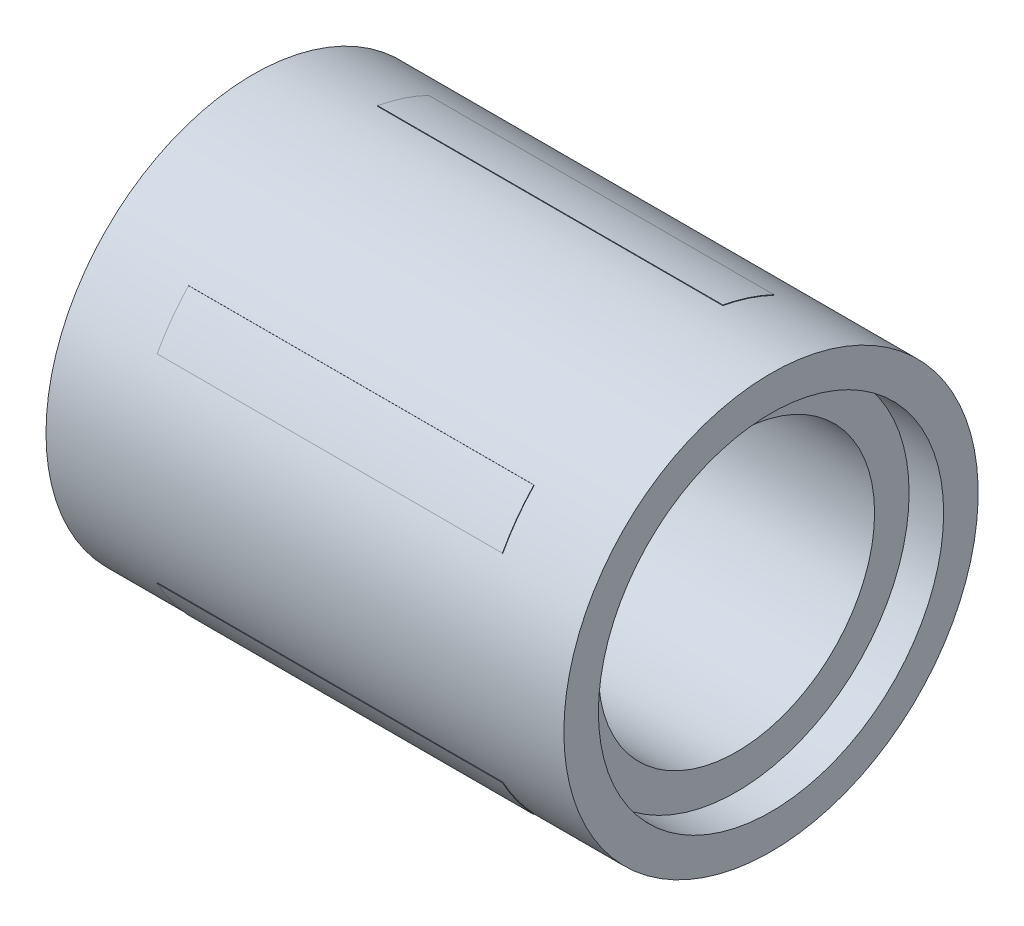
SolidWorks part; units mm, degrees
ref_plane "Alzado" through (0, 0, 0) normal (0, 0, 1) x (1, 0, 0)
ref_plane "Planta" through (0, 0, 0) normal (0, 1, 0) x (1, 0, 0)
ref_plane "Vista lateral" through (0, 0, 0) normal (1, 0, 0) x (0, 0, -1)
ref_plane "Plane1" through (0, 0, 0) normal (0, 0, 1) x (1, 0, 0)
sketch "Sketch1" plane through (0, 0, 0) normal (0, 0, 1) x (1, 0, 0)
  line L0 (-15, 10) -> (-13, 10)
  line L1 (-13, 10) -> (-13, 8)
  line L2 (-13, 8) -> (13, 8)
  line L3 (13, 8) -> (13, 10)
  line L4 (13, 10) -> (15, 10)
  line L5 (15, 10) -> (15, 12)
  line L6 (15, 12) -> (-15, 12)
  line L7 (-15, 12) -> (-15, 10)
  line L8 (15, 0) -> (-15, 0) construction
revolve "Revolve1" add sketch "Sketch1" angle 360 about L8
ref_plane "Plane2" through (0, 0, 0) normal (1, 0, 0) x (0, 0, -1)
sketch "Sketch2" plane through (0, 0, 0) normal (1, 0, 0) x (0, 0, -1)
  line L0 (-10.1299, -5.4439) -> (-10.5624, -5.7581)
  line L1 (-8.7403, -8.2661) -> (-8.3077, -7.9518)
  line L2 (2.0471, -11.3163) -> (2.2124, -11.8248)
  line L3 (5.1606, -10.8669) -> (4.9954, -10.3584)
  line L4 (11.3951, -1.55) -> (11.9297, -1.55)
  line L5 (11.9297, 1.55) -> (11.3951, 1.55)
  line L6 (4.9954, 10.3584) -> (5.1606, 10.8669)
  line L7 (2.2124, 11.8248) -> (2.0471, 11.3163)
  line L8 (-8.3077, 7.9518) -> (-8.7403, 8.2661)
  line L9 (-10.5624, 5.7581) -> (-10.1299, 5.4439)
  arc A0 (-10.1299, 5.4439) -> (-10.1299, -5.4439) centre (0, 0) ccw
  arc A1 (-10.5624, -5.7581) -> (-8.7403, -8.2661) centre (0, 0) ccw
  arc A2 (-8.3077, -7.9518) -> (2.0471, -11.3163) centre (0, 0) ccw
  arc A3 (2.2124, -11.8248) -> (5.1606, -10.8669) centre (0, 0) ccw
  arc A4 (4.9954, -10.3584) -> (11.3951, -1.55) centre (0, 0) ccw
  arc A5 (11.9297, -1.55) -> (11.9297, 1.55) centre (0, 0) ccw
  arc A6 (11.3951, 1.55) -> (4.9954, 10.3584) centre (0, 0) ccw
  arc A7 (5.1606, 10.8669) -> (2.2124, 11.8248) centre (0, 0) ccw
  arc A8 (2.0471, 11.3163) -> (-8.3077, 7.9518) centre (0, 0) ccw
  arc A9 (-8.7403, 8.2661) -> (-10.5624, 5.7581) centre (0, 0) ccw
  circle A10 centre (0, 0) radius 8.5
extrude "Boss-Extrude1" add sketch "Sketch2" against normal blind 10 and the other way blind 10
